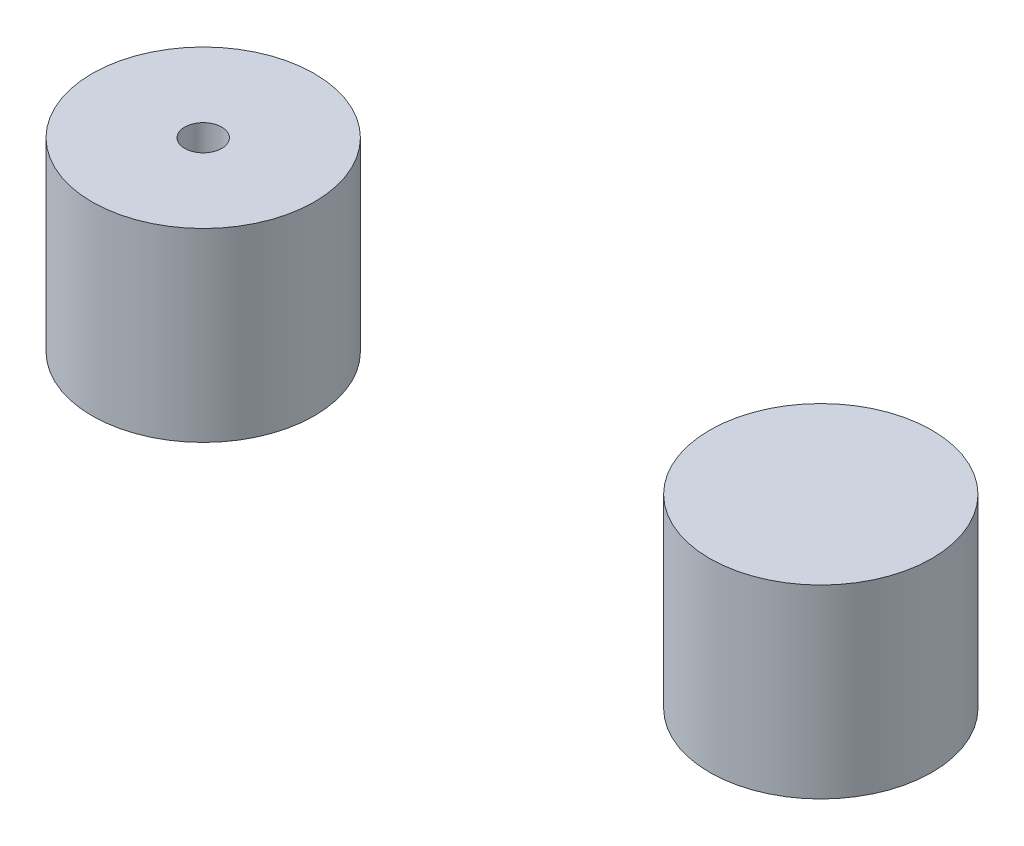
SolidWorks part; units mm, degrees
ref_plane "Front Plane" through (0, 0, 0) normal (0, 0, 1) x (1, 0, 0)
ref_plane "Top Plane" through (0, 0, 0) normal (0, 1, 0) x (1, 0, 0)
ref_plane "Right Plane" through (0, 0, 0) normal (1, 0, 0) x (0, 0, -1)
sketch "Sketch1" plane through (0, 0, 0) normal (0, 1, 0) x (1, 0, 0)
  circle A0 centre (0, 0) radius 1.8
  circle A1 centre (0, 0) radius 0.3
  circle A2 centre (10, 0) radius 1.8
  dimension "D1" = 3.6
  dimension "D2" = 0.6
  dimension "D3" = 10
extrude "Boss-Extrude1" add sketch "Sketch1" along normal blind 3
